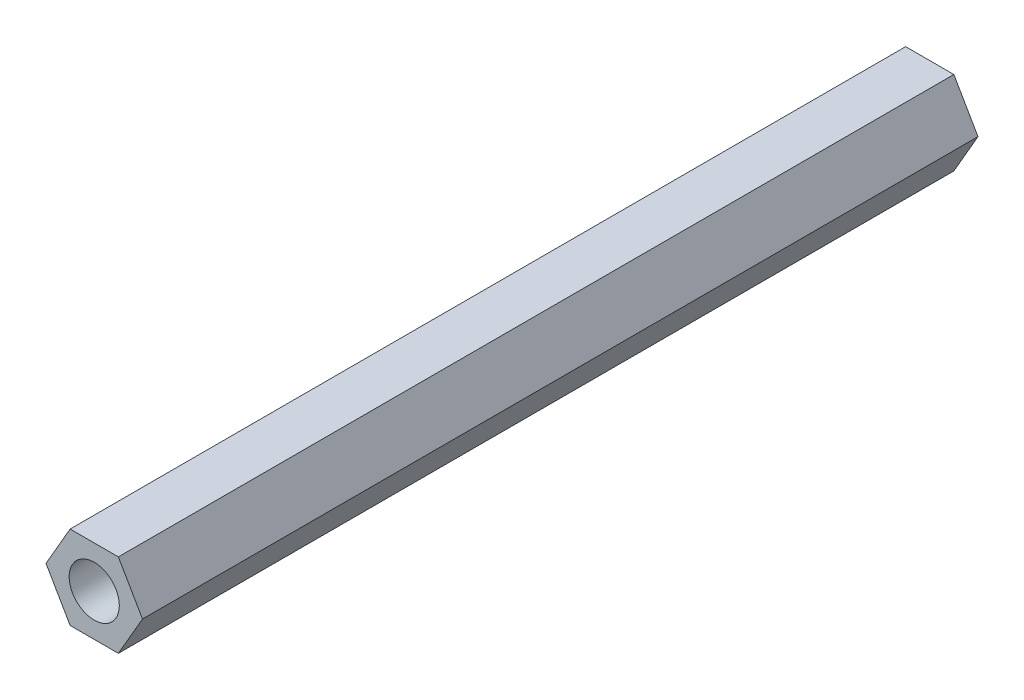
SolidWorks part; units mm, degrees
ref_plane "Alzado" through (0, 0, 0) normal (0, 0, 1) x (1, 0, 0)
ref_plane "Planta" through (0, 0, 0) normal (0, 1, 0) x (1, 0, 0)
ref_plane "Vista lateral" through (0, 0, 0) normal (1, 0, 0) x (0, 0, -1)
sketch "Croquis1" plane through (0, 0, 0) normal (0, 0, 1) x (1, 0, 0)
  line L1 (2.8868, 0) -> (1.4434, 2.5)
  line L2 (1.4434, 2.5) -> (-1.4434, 2.5)
  line L3 (-1.4434, 2.5) -> (-2.8868, 0)
  line L4 (-2.8868, 0) -> (-1.4434, -2.5)
  line L5 (-1.4434, -2.5) -> (1.4434, -2.5)
  line L6 (1.4434, -2.5) -> (2.8868, 0)
  circle A0 centre (0, 0) radius 1.5
  circle A1 centre (0, 0) radius 2.5 construction
  dimension "D1" = 3
  dimension "D2" = 5
extrude "Saliente-Extruir1" add sketch "Croquis1" against normal blind 50
